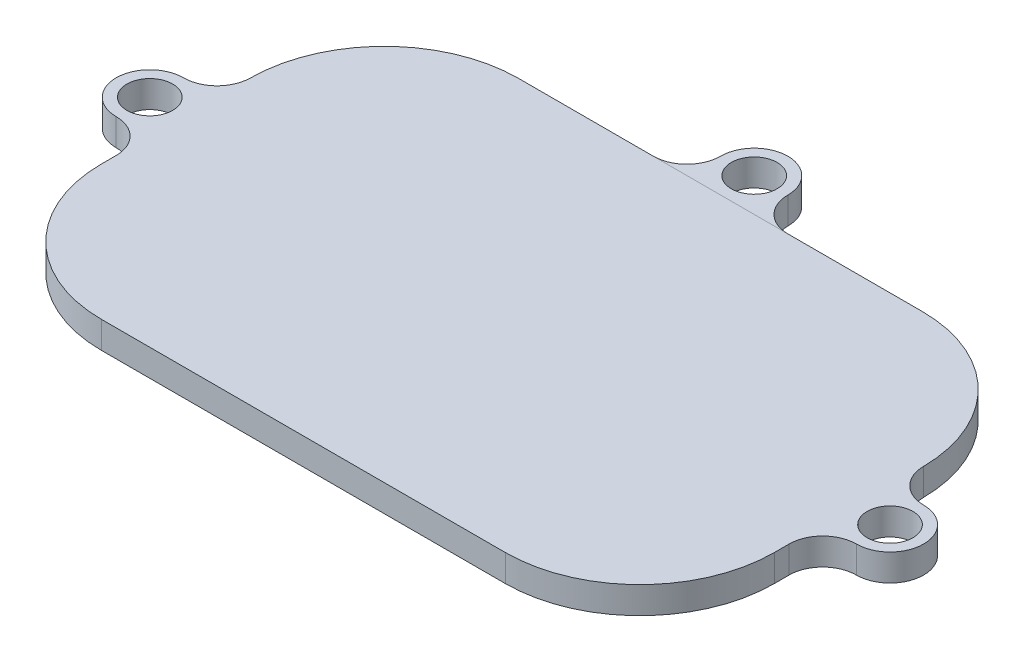
SolidWorks part; units mm, degrees
ref_plane "前视基准面" through (0, 0, 0) normal (0, 0, 1) x (1, 0, 0)
ref_plane "上视基准面" through (0, 0, 0) normal (0, 1, 0) x (1, 0, 0)
ref_plane "右视基准面" through (0, 0, 0) normal (1, 0, 0) x (0, 0, -1)
sketch "草图1" plane through (0, 0, 0) normal (0, 1, 0) x (1, 0, 0)
  line L1 (-25, 15.5) -> (25, 15.5)
  line L2 (-25, 15.5) -> (-25, -15.5)
  line L3 (-25, -15.5) -> (25, -15.5)
  line L4 (25, 15.5) -> (25, -15.5)
  line L5 (-25, 15.5) -> (25, -15.5) construction
  line L6 (-25, -15.5) -> (25, 15.5) construction
  point P0 (0, 0)
  dimension "D1" = 50
  dimension "D2" = 31
extrude "凸台-拉伸1" add sketch "草图1" along normal blind 2
sketch "草图2" plane through (0, 2, 0) normal (0, 1, 0) x (1, 0, 0)
  line L0 (0, 0) -> (0, 23.7289) construction
  line L1 (25, 15.5) -> (-25, 15.5) construction
  line L2 (-5, 15.5) -> (5, 15.5)
  arc A0 (2.5, 18) -> (-2.5, 18) centre (0, 18) ccw
  arc A1 (-5, 15.5) -> (-2.5, 18) centre (-5, 18) ccw
  arc A2 (5, 15.5) -> (2.5, 18) centre (5, 18) cw
  dimension "D1" = 5
extrude "凸台-拉伸2" add sketch "草图2" against normal up to surface (2 mm away) separate body up to face at (0, 0, 0)
sketch "草图6" plane through (0, 2, 0) normal (0, 1, 0) x (1, 0, 0)
  line L0 (0, 0) -> (0, -15.5) construction
  line L1 (-25, -15.5) -> (25, -15.5) construction
  line L3 (-25, 5.5897) -> (-25, -4.4103)
  line L12 (25, 5.5897) -> (25, -4.4103)
  arc A1 (27.5, 3.0897) -> (27.5, -1.9103) centre (27.5, 0.5897) cw construction
  circle A2 centre (-27.5, 0.5897) radius 2.5 construction
  arc A5 (-27.5, 3.0897) -> (-27.5, -1.9103) centre (-27.5, 0.5897) ccw construction
  arc A12 (-27.5, 3.0897) -> (-27.5, -1.9103) centre (-27.5, 0.5897) ccw
  arc A17 (-27.5, 3.0897) -> (-25, 5.5897) centre (-27.5, 5.5897) ccw
  arc A18 (-25, -4.4103) -> (-27.5, -1.9103) centre (-27.5, -4.4103) ccw
  arc A27 (25, -4.4103) -> (27.5, -1.9103) centre (27.5, -4.4103) cw
  arc A28 (27.5, 3.0897) -> (25, 5.5897) centre (27.5, 5.5897) cw
  arc A30 (27.5, 3.0897) -> (27.5, -1.9103) centre (27.5, 0.5897) cw
extrude "凸台-拉伸3" add sketch "草图6" against normal up to surface (2 mm away) up to face at (0, 0, 0)
hole_wizard "M3 间隙孔1" positions "草图4" profile "草图5" hole size "M3" standard "GB" end condition through all
sketch "草图4" plane through (0, 2, 0) normal (0, 1, 0) x (1, 0, 0)
  point P0 (0, 18)
  point P23 (-27.5, 0.5897)
  point P32 (27.5, 0.5897)
sketch "草图5" plane through (0, 2, -18) normal (1, 0, 0) x (0, 0, 1)
  line L0 (0, 0) -> (0, 2)
  line L1 (0, 2) -> (1.7, 2)
  line L2 (1.7, 2) -> (1.7, 0)
  line L5 (1.7, 0) -> (0, 0)
  line L11 (0, -6.35) -> (0, 107.95) construction
  dimension "通孔孔直径" = 3.4
  dimension "通孔孔深度" = 2
fillet "圆角1" radius 10 4 edges at (25, 1, -15.5) (-25, 1, -15.5) (25, 1, 15.5) (-25, 1, 15.5)
